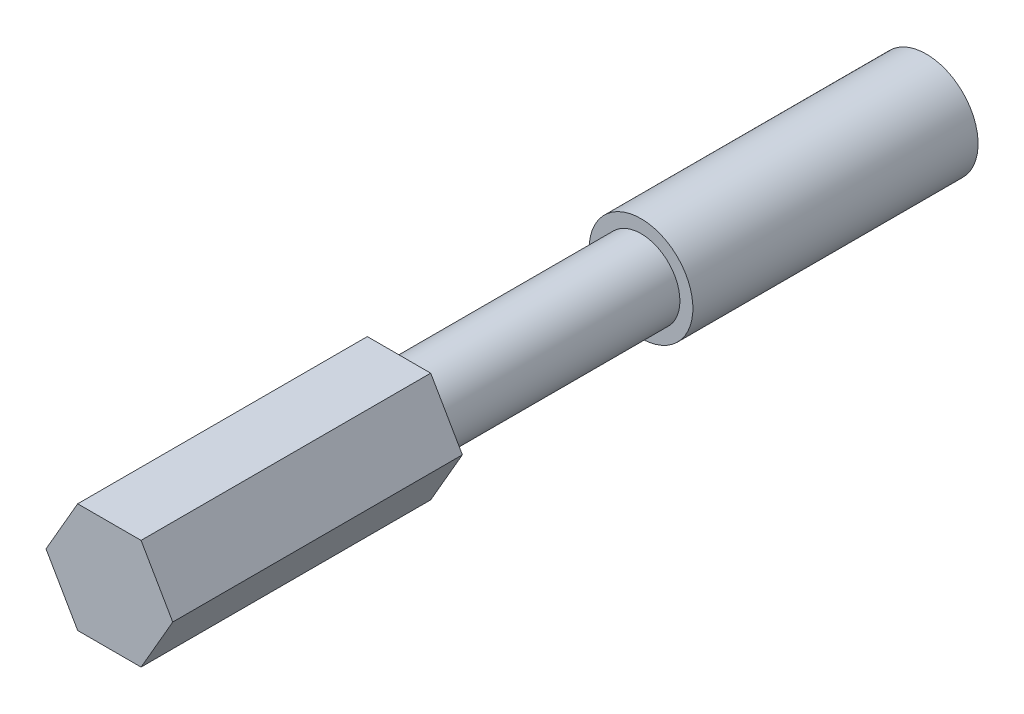
SolidWorks part; units mm, degrees
ref_plane "Front Plane" through (0, 0, 0) normal (0, 0, 1) x (1, 0, 0)
ref_plane "Top Plane" through (0, 0, 0) normal (0, 1, 0) x (1, 0, 0)
ref_plane "Right Plane" through (0, 0, 0) normal (1, 0, 0) x (0, 0, -1)
sketch "Sketch1" plane through (0, 0, 0) normal (0, 0, 1) x (1, 0, 0)
  line L1 (3.6662, -6.35) -> (7.3323, 0)
  line L2 (7.3323, 0) -> (3.6662, 6.35)
  line L3 (3.6662, 6.35) -> (-3.6662, 6.35)
  line L4 (-3.6662, 6.35) -> (-7.3323, 0)
  line L5 (-7.3323, 0) -> (-3.6662, -6.35)
  line L6 (-3.6662, -6.35) -> (3.6662, -6.35)
  circle A0 centre (0, 0) radius 6.35 construction
  dimension "D1" = 12.7
extrude "Boss-Extrude1" add sketch "Sketch1" along normal blind 27
sketch "Sketch2" plane through (0, 0, 0) normal (0, 0, -1) x (-1, 0, 0)
  circle A0 centre (0, 0) radius 4.5
  dimension "D1" = 9
extrude "Boss-Extrude2" add sketch "Sketch2" along normal blind 61
sketch "Sketch3" plane through (0, 0, -61) normal (0, 0, -1) x (-1, 0, 0)
  line L0 (-5, 3) -> (-2.6458, 3) construction
  line L1 (-2.6458, 3) -> (2.6458, 3)
  line L2 (-5, 3) -> (-5, -3) construction
  line L3 (-2.6458, -3) -> (2.6458, -3)
  line L4 (5, 3) -> (5, -3) construction
  line L5 (-5, 3) -> (5, -3) construction
  line L6 (-5, -3) -> (5, 3) construction
  line L7 (-5, -3) -> (-2.6458, -3) construction
  line L8 (2.6458, -3) -> (5, -3) construction
  line L9 (2.6458, 3) -> (5, 3) construction
  arc A0 (-2.6458, 3) -> (-2.6458, -3) centre (0, 0) ccw
  arc A1 (2.6458, 3) -> (-2.6458, 3) centre (0, 0) ccw construction
  arc A2 (-2.6458, -3) -> (2.6458, -3) centre (0, 0) ccw construction
  arc A3 (2.6458, -3) -> (2.6458, 3) centre (0, 0) ccw
  point P0 (0, 0)
  dimension "D1" = 8
  dimension "D2" = 6
  dimension "D3" = 10
extrude "Cut-Extrude1" cut sketch "Sketch3" against normal blind 14
sketch "Sketch4" plane through (0, 0, -61) normal (0, 0, -1) x (-1, 0, 0)
  line L0 (-2.6458, -3) -> (2.6458, -3) construction
  line L1 (2.6458, 3) -> (-2.6458, 3) construction
  line L2 (-2.6458, -3) -> (2.6458, -3)
  line L3 (2.6458, 3) -> (-2.6458, 3)
  arc A0 (-2.6458, 3) -> (-2.6458, -3) centre (0, 0) ccw construction
  circle A1 centre (0, 0) radius 4.5
  circle A2 centre (0, 0) radius 4.5 construction
  arc A3 (2.6458, -3) -> (2.6458, 3) centre (0, 0) ccw construction
  arc A4 (-2.6458, 3) -> (-2.6458, -3) centre (0, 0) ccw
  arc A5 (2.6458, -3) -> (2.6458, 3) centre (0, 0) ccw
  circle A6 centre (0, 0) radius 6
  dimension "D2" = 12
  dimension "D1" = 0
extrude "Boss-Extrude3" add sketch "Sketch4" against normal blind 33
sketch "Sketch5" plane through (0, 0, 27) normal (0, 0, 1) x (1, 0, 0)
  line L0 (-3.6662, 6.35) -> (-7.3323, 0)
  line L1 (-7.3323, 0) -> (-3.6662, -6.35)
  line L2 (-3.6662, -6.35) -> (3.6662, -6.35)
  line L3 (3.6662, -6.35) -> (7.3323, 0)
  line L4 (7.3323, 0) -> (3.6662, 6.35)
  line L5 (3.6662, 6.35) -> (-3.6662, 6.35)
extrude "Boss-Extrude4" add sketch "Sketch5" along normal blind 6.51
